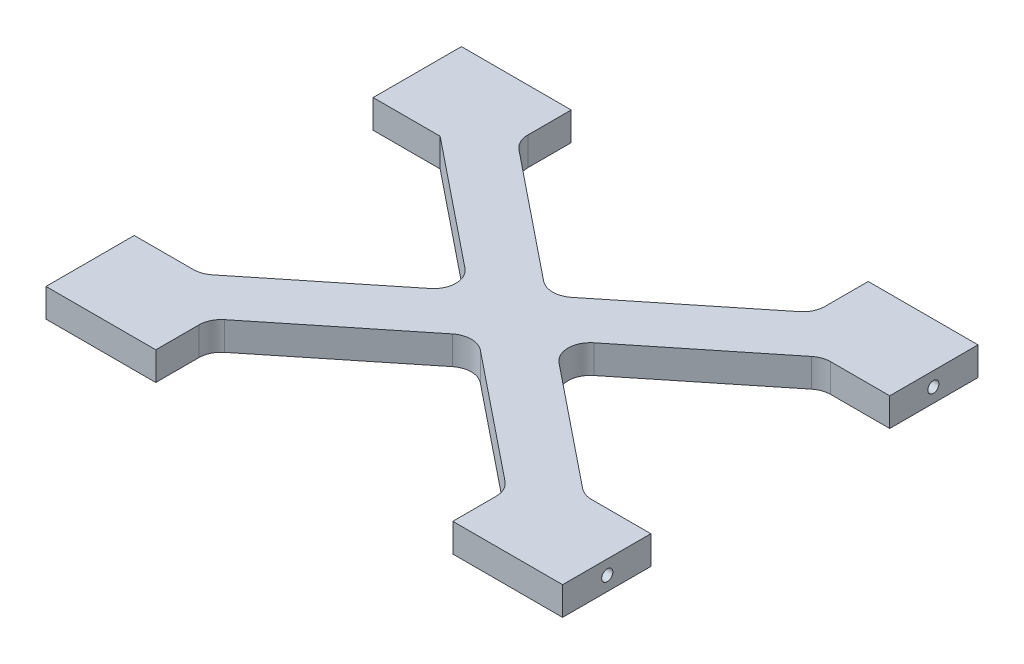
SolidWorks part; units mm, degrees
material "6061 Alloy"
ref_plane "Front Plane" through (0, 0, 0) normal (0, 0, 1) x (1, 0, 0)
ref_plane "Top Plane" through (0, 0, 0) normal (0, 1, 0) x (1, 0, 0)
ref_plane "Right Plane" through (0, 0, 0) normal (1, 0, 0) x (0, 0, -1)
sketch "Sketch1" plane through (0, 0, 0) normal (0, 1, 0) x (1, 0, 0)
  line L1 (57.825, 46.5) -> (-57.825, 46.5) construction
  line L2 (57.825, 46.5) -> (57.825, -46.5) construction
  line L3 (57.825, -46.5) -> (-57.825, -46.5) construction
  line L4 (-57.825, 46.5) -> (-57.825, -46.5) construction
  line L5 (-57.825, 46.5) -> (57.825, -46.5) construction
  line L6 (-57.825, 26.7384) -> (-42.825, 26.7384)
  line L36 (-42.825, 26.7384) -> (-9.5745, 0)
  line L37 (-9.5745, 0) -> (-42.825, -26.7384)
  line L38 (-42.825, -26.7384) -> (-57.825, -26.7384)
  line L39 (-57.825, -26.7384) -> (-57.825, -46.5)
  line L40 (-57.825, -46.5) -> (-33.2505, -46.5)
  line L41 (-33.2505, -46.5) -> (-33.2505, -34.4377)
  line L42 (-33.2505, -34.4377) -> (0, -7.6993)
  line L43 (0, -7.6993) -> (33.2505, -34.4377)
  line L44 (33.2505, -34.4377) -> (33.2505, -46.5)
  line L45 (33.2505, -46.5) -> (57.825, -46.5)
  line L46 (57.825, -46.5) -> (57.825, -26.7384)
  line L47 (57.825, -26.7384) -> (42.825, -26.7384)
  line L48 (42.825, -26.7384) -> (9.5745, 0)
  line L49 (9.5745, 0) -> (42.825, 26.7384)
  line L50 (42.825, 26.7384) -> (57.825, 26.7384)
  line L51 (57.825, 26.7384) -> (57.825, 46.5)
  line L52 (57.825, 46.5) -> (33.2505, 46.5)
  line L53 (33.2505, 46.5) -> (33.2505, 34.4377)
  line L54 (33.2505, 34.4377) -> (0, 7.6993)
  line L55 (0, 7.6993) -> (-33.2505, 34.4377)
  line L56 (-33.2505, 34.4377) -> (-33.2505, 46.5)
  line L57 (-33.2505, 46.5) -> (-57.825, 46.5)
  line L58 (-57.825, 46.5) -> (-57.825, 26.7384)
  line L59 (-57.825, -46.5) -> (57.825, 46.5) construction
  line L65 (42.825, 26.7384) -> (33.2505, 34.4377) construction
  dimension "D1" = 115.65
  dimension "D2" = 93
  dimension "D3" = 12
  dimension "D4" = 15
extrude "Boss-Extrude1" add sketch "Sketch1" along normal blind 6.35
fillet "Fillet1" radius 5 11 edges at (-33.2505, 3.175, -34.4377) (33.2505, 3.175, -34.4377) (42.825, 3.175, -26.7384) (42.825, 3.175, 26.7384) (33.2505, 3.175, 34.4377) (-33.2505, 3.175, 34.4377) (-42.825, 3.175, 26.7384) (-9.5745, 3.175, 0) (0, 3.175, -7.6993) (9.5745, 3.175, 0) (0, 3.175, 7.6993)
sketch "Sketch2" plane through (57.825, 0, 0) normal (1, 0, 0) x (0, 0, -1)
  line L0 (46.5, 6.35) -> (46.5, 0) construction
  line L1 (0, 0) -> (0, 6.35) construction
  line L2 (3.8964, 6.35) -> (-3.8964, 6.35) construction
  circle A0 centre (36.5, 3.175) radius 1.25
  circle A1 centre (-36.5, 3.175) radius 1.25
  point P7 (46.5, 3.175)
  dimension "D1" = 2.5
  dimension "D2" = 10
extrude "Cut-Extrude1" cut sketch "Sketch2" against normal blind 20
mirror "Mirror1" about plane through (0, 0, 0) normal (1, 0, 0) of "Cut-Extrude1"
equation "\"L1L\"=500"
equation "\"L1Thick\"=6.35"
equation "\"Harm-Drive-Outer\"=74.5"
equation "\"L1-Spacing\"=115.65"
equation "\"L-Bracket-HoleToWall\"=12.5"
equation "\"L-Bracket-HoleToSide\"=11"
equation "\"Bracket-Hole-D\"=6.8"
equation "\"D1@Sketch1\"=\"L1-Spacing\""
